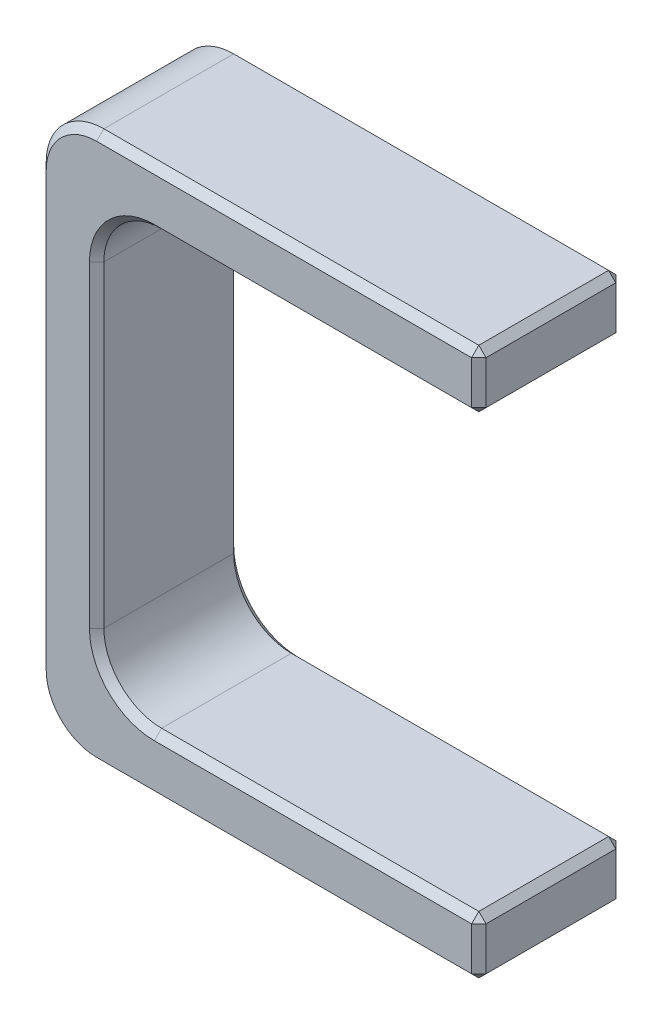
SolidWorks part; units mm, degrees
ref_plane "Top" through (0, 0, 0) normal (0, 0, 1) x (1, 0, 0)
ref_plane "Front" through (0, 0, 0) normal (0, 1, 0) x (1, 0, 0)
ref_plane "Right" through (0, 0, 0) normal (1, 0, 0) x (0, 0, -1)
sketch "Sketch1" plane through (0, 0, 0) normal (0, 0, 1) x (1, 0, 0)
  line L0 (0, 0) -> (0, 38)
  line L1 (0, 38) -> (30.5, 38)
  line L2 (30.5, 38) -> (30.5, 34)
  line L3 (30.5, 34) -> (4, 34)
  line L4 (4, 34) -> (4, 4)
  line L5 (4, 4) -> (30.5, 4)
  line L6 (30.5, 4) -> (30.5, 0)
  line L7 (30.5, 0) -> (0, 0)
  dimension "D1" = 30
  dimension "D2" = 26.5
  dimension "D3" = 4
  dimension "D4" = 4
  dimension "D5" = 4
extrude "Boss-Extrude1" add sketch "Sketch1" along normal blind 10
fillet "Fillet1" radius 4 4 edges at (4, 4, 5) (4, 34, 5) (0, 38, 5) (0, 0, 5)
chamfer "Chamfer1" distance 0.5 angle 45 28 edges at (30.5, 36, 10) (19.25, 34, 10) (5.1716, 32.8284, 10) (4, 19, 10) (5.1716, 5.1716, 10) (19.25, 4, 10) (30.5, 2, 10) (17.25, 0, 10) (1.1716, 1.1716, 10) (0, 19, 10) (1.1716, 36.8284, 10) (17.25, 38, 10) (1.1716, 1.1716, 0) (17.25, 0, 0) (30.5, 0, 5) (30.5, 2, 0) (30.5, 4, 5) (19.25, 4, 0) (5.1716, 5.1716, 0) (4, 19, 0) (5.1716, 32.8284, 0) (19.25, 34, 0) (0, 19, 0) (1.1716, 36.8284, 0) (17.25, 38, 0) (30.5, 38, 5) (30.5, 36, 0) (30.5, 34, 5)
